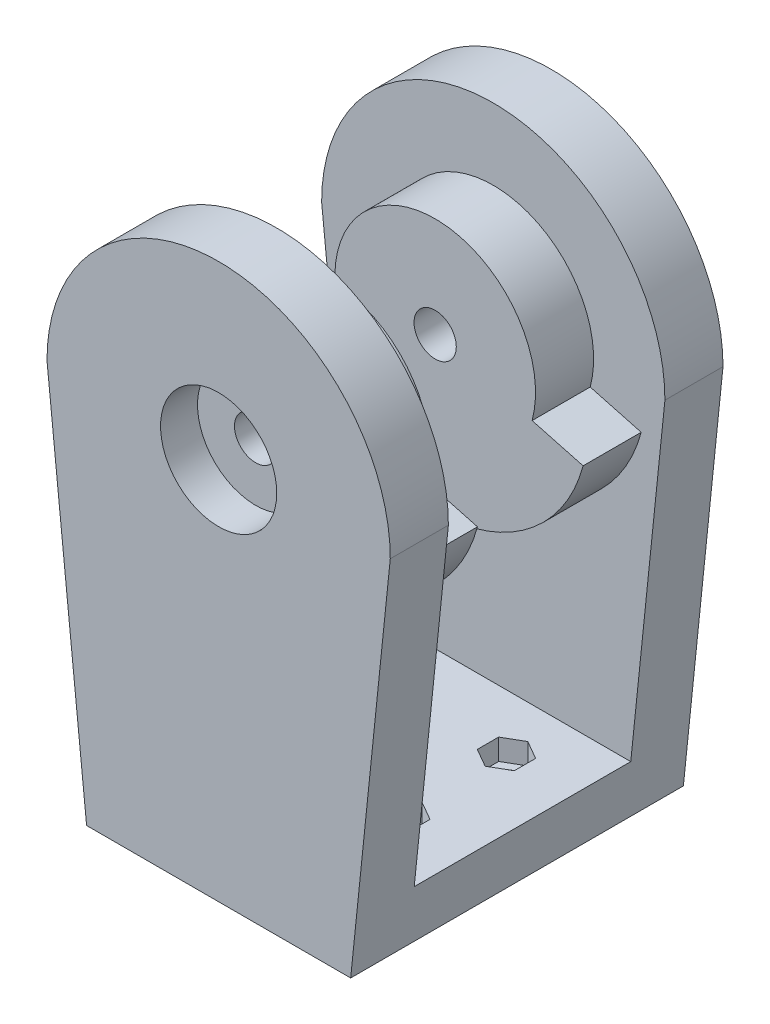
SolidWorks part; units mm, degrees
ref_plane "Alzado" through (0, 0, 0) normal (0, 0, 1) x (1, 0, 0)
ref_plane "Planta" through (0, 0, 0) normal (0, 1, 0) x (1, 0, 0)
ref_plane "Vista lateral" through (0, 0, 0) normal (1, 0, 0) x (0, 0, -1)
sketch "Croquis1" plane through (0, 0, 0) normal (0, 0, 1) x (1, 0, 0)
  line L0 (0, 0) -> (0, -32.5) construction
  line L1 (0, -32.5) -> (0, -72.5) construction
  line L2 (-32.5, 0) -> (32.5, 0) construction
  line L3 (-32.5, 0) -> (-25, -72.5)
  line L4 (-25, -72.5) -> (25, -72.5)
  line L5 (25, -72.5) -> (32.5, 0)
  arc A0 (32.5, 0) -> (-32.5, 0) centre (0, 0) ccw
  dimension "D1" = 65
  dimension "D2" = 40
  dimension "D3" = 50
  dimension "D4" = 25
  dimension "D5" = 72.5
extrude "Saliente-Extruir1" add sketch "Croquis1" along normal blind 11 contours L5 A0 L3 L4
sketch "Croquis2" plane through (0, 0, 11) normal (0, 0, 1) x (1, 0, 0)
  circle A0 centre (0, 0) radius 11
  dimension "D1" = 22
extrude "Cortar-Extruir1" cut sketch "Croquis2" against normal blind 7
sketch "Croquis3" plane through (0, 0, 0) normal (0, 0, -1) x (-1, 0, 0)
  circle A0 centre (0, 0) radius 19
  dimension "D1" = 38
extrude "Saliente-Extruir2" add sketch "Croquis3" along normal blind 10
sketch "Croquis4" plane through (0, 0, 4) normal (0, 0, 1) x (1, 0, 0)
  circle A0 centre (0, 0) radius 4
  dimension "D1" = 8
extrude "Cortar-Extruir2" cut sketch "Croquis4" against normal blind 18
sketch "Croquis5" plane through (0, 0, 0) normal (0, 0, -1) x (-1, 0, 0)
  line L0 (-25, -72.5) -> (25, -72.5)
  line L1 (25, -72.5) -> (26.0345, -62.5)
  line L2 (32.5, 0) -> (25, -72.5) construction
  line L3 (26.0345, -62.5) -> (-26.0345, -62.5)
  line L4 (-25, -72.5) -> (-32.5, 0) construction
  line L5 (-26.0345, -62.5) -> (-25, -72.5)
  dimension "D1" = 10
extrude "Saliente-Extruir3" add sketch "Croquis5" along normal blind 52
sketch "Croquis6" plane through (0, 0, -52) normal (0, 0, -1) x (-1, 0, 0)
  line L0 (25, -72.5) -> (32.5, 0)
  line L1 (25, -72.5) -> (-25, -72.5)
  line L2 (-25, -72.5) -> (-32.5, 0)
  arc A0 (-32.5, 0) -> (32.5, 0) centre (0, 0) cw
extrude "Saliente-Extruir4" add sketch "Croquis6" against normal blind 11
sketch "Croquis7" plane through (0, 0, -52) normal (0, 0, -1) x (-1, 0, 0)
  circle A0 centre (0, 0) radius 4
  dimension "D1" = 8
extrude "Cortar-Extruir3" cut sketch "Croquis7" against normal blind 22
sketch "Croquis8" plane through (0, 0, -41) normal (0, 0, 1) x (1, 0, 0)
  circle A0 centre (0, 0) radius 19
  dimension "D1" = 38
extrude "Saliente-Extruir5" add sketch "Croquis8" along normal blind 11
sketch "Croquis10" plane through (0, 0, -52) normal (0, 0, -1) x (-1, 0, 0)
  circle A0 centre (0, 0) radius 4
  dimension "D1" = 8
extrude "Cortar-Extruir5" cut sketch "Croquis10" against normal through all
sketch "Croquis11" plane through (0, 0, -52) normal (0, 0, -1) x (-1, 0, 0)
  circle A0 centre (0, 0) radius 11
extrude "Cortar-Extruir6" cut sketch "Croquis11" against normal blind 7
sketch "Croquis12" plane through (0, 0, 0) normal (0, 0, -1) x (-1, 0, 0)
  line L0 (0, 32.5) -> (0, -62.5) construction
  line L1 (26.0345, -62.5) -> (-26.0345, -62.5) construction
  line L2 (-32.5, 0) -> (32.5, 0) construction
  line L3 (0, 0) -> (25.2101, -17.6523) construction
  line L4 (0, 0) -> (-26.4598, -7.0899) construction
  line L5 (-18.3526, -4.9176) -> (-28.0118, -7.5058)
  line L6 (15.5639, -10.898) -> (23.7554, -16.6337)
  arc A0 (32.5, 0) -> (-32.5, 0) centre (0, 0) ccw construction
  arc A1 (-28.0118, -7.5058) -> (23.7554, -16.6337) centre (0, 0) ccw
  circle A2 centre (0, 0) radius 19 construction
  arc A3 (-18.3526, -4.9176) -> (15.5639, -10.898) centre (0, 0) ccw
  dimension "D3" = 10
  dimension "D4" = 19
  dimension "D1" = 35
  dimension "D2" = 15
extrude "Saliente-Extruir6" add sketch "Croquis12" along normal blind 10
sketch "Croquis13" plane through (0, 0, -41) normal (0, 0, 1) x (1, 0, 0)
  line L0 (-32.5, 0) -> (32.5, 0) construction
  line L1 (0, 32.5) -> (0, -72.5) construction
  line L2 (25, -72.5) -> (-25, -72.5) construction
  line L3 (0, 0) -> (32.2052, -8.6294) construction
  line L4 (0, 0) -> (-28.4547, -19.9242) construction
  line L5 (-15.5639, -10.898) -> (-23.7554, -16.6337)
  line L6 (18.3526, -4.9176) -> (28.0118, -7.5058)
  arc A0 (32.5, 0) -> (-32.5, 0) centre (0, 0) ccw construction
  arc A1 (-23.7554, -16.6337) -> (28.0118, -7.5058) centre (0, 0) ccw
  circle A2 centre (0, 0) radius 19 construction
  circle A4 centre (0, 0) radius 19 construction
  arc A5 (-15.5639, -10.898) -> (18.3526, -4.9176) centre (0, 0) ccw
  dimension "D3" = 10
  dimension "D1" = 15
  dimension "D2" = 35
extrude "Saliente-Extruir7" add sketch "Croquis13" along normal blind 11
sketch "Croquis14" plane through (0, -62.5, 0) normal (0, 1, 0) x (1, 0, 0)
  line L0 (-26.0345, 20.5) -> (26.0345, 20.5) construction
  line L1 (-26.0345, 41) -> (-26.0345, 0) construction
  line L2 (26.0345, 41) -> (26.0345, 0) construction
  line L3 (0, 41) -> (0, 0) construction
  line L4 (26.0345, 41) -> (-26.0345, 41) construction
  line L5 (-13, 41) -> (-13, 0) construction
  line L6 (-26.0345, 0) -> (26.0345, 0) construction
  line L7 (13, 41) -> (13, 0) construction
  line L8 (-26.0345, 10.5) -> (26.0345, 10.5) construction
  line L9 (-26.0345, 30.5) -> (26.0345, 30.5) construction
  circle A0 centre (-13, 30.5) radius 2
  circle A1 centre (13, 30.5) radius 2
  circle A2 centre (13, 10.5) radius 2
  circle A3 centre (-13, 10.5) radius 2
  dimension "D3" = 4
  dimension "D1" = 13
  dimension "D2" = 10
extrude "Cortar-Extruir7" cut sketch "Croquis14" against normal blind 11
sketch "Croquis15" plane through (0, -62.5, 0) normal (0, 1, 0) x (1, 0, 0)
  line L0 (-26.0345, 20.5) -> (26.0345, 20.5) construction
  line L1 (-26.0345, 41) -> (-26.0345, 0) construction
  line L2 (26.0345, 41) -> (26.0345, 0) construction
  line L3 (0, 41) -> (0, 0) construction
  line L4 (26.0345, 41) -> (-26.0345, 41) construction
  line L5 (13, 26.4585) -> (9.5, 28.4793)
  line L6 (-9.5, 28.4793) -> (-9.5, 32.5207)
  line L7 (-9.5, 32.5207) -> (-13, 34.5415)
  line L8 (-13, 34.5415) -> (-16.5, 32.5207)
  line L9 (-16.5, 32.5207) -> (-16.5, 28.4793)
  line L10 (-16.5, 28.4793) -> (-13, 26.4585)
  line L11 (-13, 26.4585) -> (-9.5, 28.4793)
  line L12 (16.5, 28.4793) -> (13, 26.4585)
  line L13 (16.5, 32.5207) -> (16.5, 28.4793)
  line L14 (13, 34.5415) -> (16.5, 32.5207)
  line L15 (9.5, 32.5207) -> (13, 34.5415)
  line L16 (9.5, 28.4793) -> (9.5, 32.5207)
  line L17 (16.5, 12.5207) -> (13, 14.5415)
  line L18 (16.5, 8.4793) -> (16.5, 12.5207)
  line L19 (13, 6.4585) -> (16.5, 8.4793)
  line L20 (9.5, 8.4793) -> (13, 6.4585)
  line L21 (9.5, 12.5207) -> (9.5, 8.4793)
  line L22 (13, 14.5415) -> (9.5, 12.5207)
  line L23 (-13, 14.5415) -> (-9.5, 12.5207)
  line L24 (-16.5, 12.5207) -> (-13, 14.5415)
  line L25 (-16.5, 8.4793) -> (-16.5, 12.5207)
  line L26 (-13, 6.4585) -> (-16.5, 8.4793)
  line L27 (-9.5, 8.4793) -> (-13, 6.4585)
  line L28 (-9.5, 12.5207) -> (-9.5, 8.4793)
  circle A0 centre (-13, 30.5) radius 3.5 construction
  dimension "D1" = 7
extrude "Cortar-Extruir8" cut sketch "Croquis15" against normal blind 4
